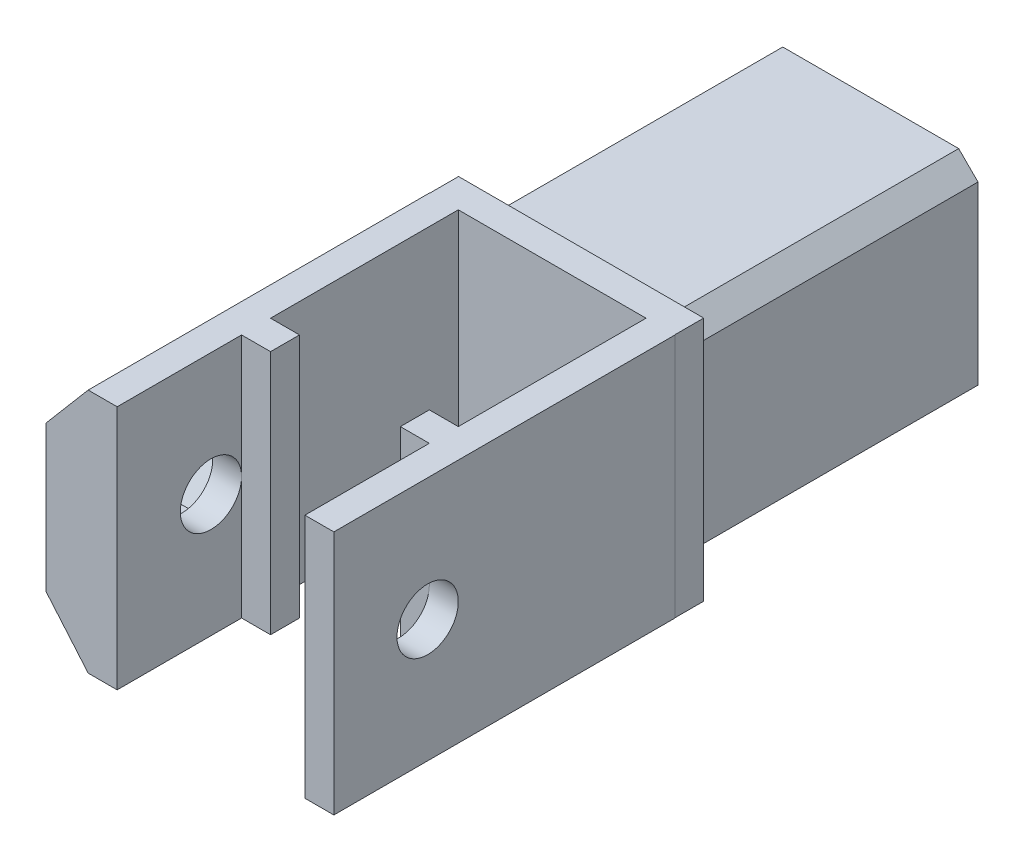
SolidWorks part; units mm, degrees
ref_plane "Front Plane" through (0, 0, 0) normal (0, 0, 1) x (1, 0, 0)
ref_plane "Top Plane" through (0, 0, 0) normal (0, 1, 0) x (1, 0, 0)
ref_plane "Right Plane" through (0, 0, 0) normal (1, 0, 0) x (0, 0, -1)
sketch "Sketch1" plane through (0, 0, 0) normal (0, 0, 1) x (1, 0, 0)
  line L1 (-11.1125, -11.1125) -> (11.1125, -11.1125)
  line L2 (-11.1125, -11.1125) -> (-11.1125, 11.1125)
  line L3 (-11.1125, 11.1125) -> (11.1125, 11.1125)
  line L4 (11.1125, -11.1125) -> (11.1125, 11.1125)
  line L5 (-11.1125, -11.1125) -> (11.1125, 11.1125) construction
  line L6 (-11.1125, 11.1125) -> (11.1125, -11.1125) construction
  point P0 (0, 0)
  dimension "D1" = 22.225
extrude "Boss-Extrude1" add sketch "Sketch1" along normal blind 30
sketch "Sketch3" plane through (0, 0, 30) normal (0, 0, 1) x (1, 0, 0)
  line L1 (-12.7, -12.7) -> (12.7, -12.7)
  line L2 (-12.7, -12.7) -> (-12.7, 12.7)
  line L3 (-12.7, 12.7) -> (12.7, 12.7)
  line L4 (12.7, -12.7) -> (12.7, 12.7)
  line L5 (-12.7, -12.7) -> (12.7, 12.7) construction
  line L6 (-12.7, 12.7) -> (12.7, -12.7) construction
  point P0 (0, 0)
  dimension "D1" = 25.4
extrude "Boss-Extrude2" add sketch "Sketch3" along normal blind 3
sketch "Sketch4" plane through (0, 12.7, 0) normal (0, 1, 0) x (1, 0, 0)
  line L0 (-12.725, -33) -> (-12.725, -68.34)
  line L1 (12.7, -33) -> (-12.7, -33) construction
  line L2 (-12.725, -68.34) -> (-9.725, -68.34)
  line L3 (-9.725, -68.34) -> (-9.725, -55.45)
  line L4 (-9.725, -55.45) -> (-6.725, -55.45)
  line L5 (-6.725, -55.45) -> (-6.725, -52.45)
  line L6 (-6.725, -52.45) -> (-9.725, -52.45)
  line L7 (-9.725, -52.45) -> (-9.725, -33)
  line L8 (-9.725, -33) -> (-12.725, -33)
  line L9 (0, -33) -> (0, -68.34) construction
  line L10 (9.725, -33) -> (12.725, -33)
  line L11 (9.725, -52.45) -> (9.725, -33)
  line L12 (6.725, -52.45) -> (9.725, -52.45)
  line L13 (6.725, -55.45) -> (6.725, -52.45)
  line L14 (9.725, -55.45) -> (6.725, -55.45)
  line L15 (9.725, -68.34) -> (9.725, -55.45)
  line L16 (12.725, -68.34) -> (9.725, -68.34)
  line L17 (12.725, -33) -> (12.725, -68.34)
  line L18 (-9.725, -33) -> (9.725, -33) construction
  dimension "D1" = 19.45
  dimension "D2" = 3
  dimension "D3" = 3
  dimension "D4" = 12.89
extrude "Boss-Extrude3" add sketch "Sketch4" against normal up to surface (25.4 mm away) up to face at (0, -12.7, 31.5)
sketch "Sketch6" plane through (0, 0, 68.34) normal (0, 0, 1) x (1, 0, 0)
  line L0 (-12.725, -12.7) -> (-17.095, -7.555)
  line L1 (-9.725, -12.7) -> (-12.725, -12.7) construction
  line L2 (-17.095, -7.555) -> (-17.095, 7.555)
  line L3 (-17.095, 7.555) -> (-12.725, 12.7)
  line L4 (-12.725, 12.7) -> (-12.725, -12.7)
  line L7 (-17.095, 0) -> (-12.725, 0) construction
  line L9 (-12.725, 12.7) -> (-9.725, 12.7) construction
  dimension "D1" = 15.11
  dimension "D2" = 4.37
extrude "Boss-Extrude4" add sketch "Sketch6" against normal blind 19.43
sketch "Sketch5" plane through (9.725, 0, 0) normal (-1, 0, 0) x (0, 0, 1)
  line L0 (55.45, -12.7) -> (55.45, 12.7) construction
  circle A0 centre (58.625, 0) radius 3.175
  dimension "D1" = 6.35
extrude "Cut-Extrude1" cut sketch "Sketch5" against normal through all both and the other way through all
sketch "Sketch7" plane through (-17.095, 0, 0) normal (-1, 0, 0) x (0, 0, 1)
  line L1 (61.9765, 5.805) -> (55.2735, 5.805)
  line L2 (55.2735, 5.805) -> (51.922, 0)
  line L3 (51.922, 0) -> (55.2735, -5.805)
  line L4 (55.2735, -5.805) -> (61.9765, -5.805)
  line L5 (61.9765, -5.805) -> (65.328, 0)
  line L6 (65.328, 0) -> (61.9765, 5.805)
  circle A0 centre (58.625, 0) radius 5.805 construction
  dimension "D1" = 11.61
extrude "Cut-Extrude2" cut sketch "Sketch7" against normal blind 4.38
chamfer "Chamfer1" distance 2 angle 45 4 edges at (-11.1125, -11.1125, 15) (-11.1125, 11.1125, 15) (11.1125, -11.1125, 15) (11.1125, 11.1125, 15)
equation "\"D4@Sketch4\"=.25in/2+12.83/2+3+.3"
